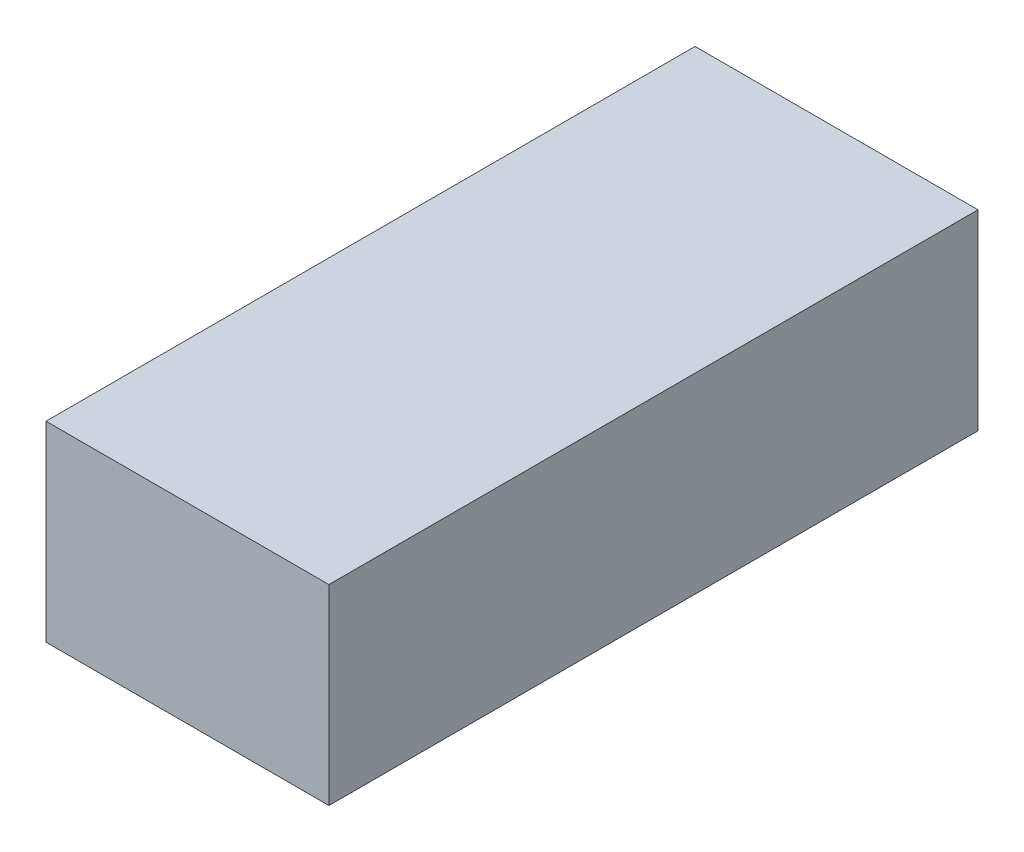
SolidWorks part; units mm, degrees
ref_plane "Front Plane" through (0, 0, 0) normal (0, 0, 1) x (1, 0, 0)
ref_plane "Top Plane" through (0, 0, 0) normal (0, 1, 0) x (1, 0, 0)
ref_plane "Right Plane" through (0, 0, 0) normal (1, 0, 0) x (0, 0, -1)
sketch "Sketch1" plane through (0, 0, 0) normal (0, 1, 0) x (1, 0, 0)
  line L1 (0, 0) -> (34, 0)
  line L2 (0, 0) -> (0, 78)
  line L3 (0, 78) -> (34, 78)
  line L4 (34, 0) -> (34, 78)
  dimension "D1" = 34
  dimension "D2" = 78
extrude "Boss-Extrude1" add sketch "Sketch1" along normal blind 23
